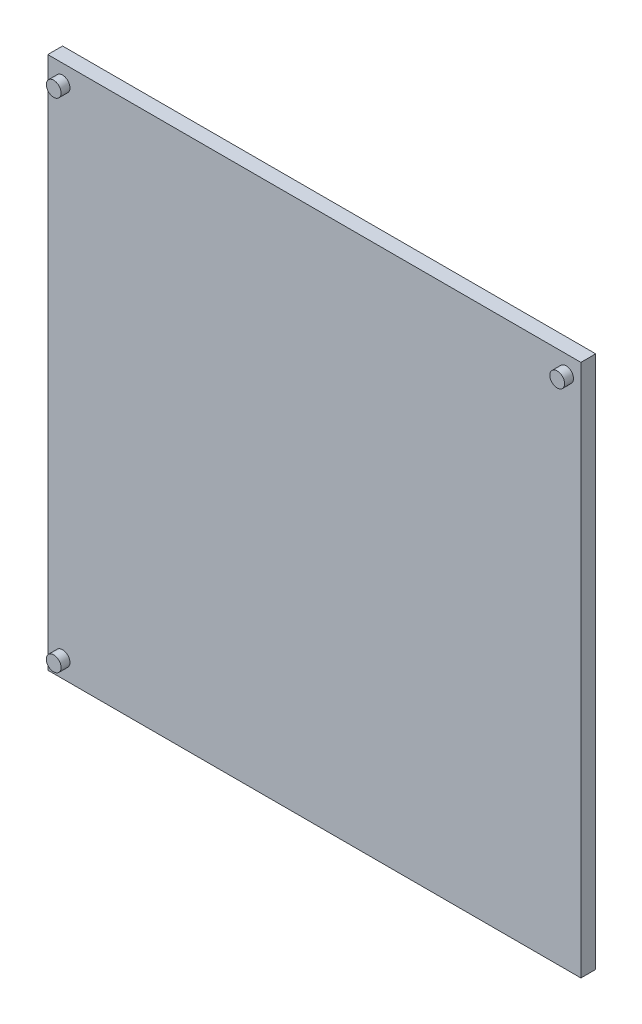
SolidWorks part; units mm, degrees
ref_plane "Front Plane" through (0, 0, 0) normal (0, 0, 1) x (1, 0, 0)
ref_plane "Top Plane" through (0, 0, 0) normal (0, 1, 0) x (1, 0, 0)
ref_plane "Right Plane" through (0, 0, 0) normal (1, 0, 0) x (0, 0, -1)
sketch "Sketch1" plane through (0, 0, 0) normal (0, 0, 1) x (1, 0, 0)
  line L1 (-45, -45) -> (45, -45)
  line L2 (-45, -45) -> (-45, 45)
  line L3 (-45, 45) -> (45, 45)
  line L4 (45, -45) -> (45, 45)
  line L5 (-45, -45) -> (45, 45) construction
  line L6 (-45, 45) -> (45, -45) construction
  point P0 (0, 0)
  dimension "D1" = 90
  dimension "D2" = 90
extrude "Boss-Extrude1" add sketch "Sketch1" along normal blind 2.5
sketch "Sketch2" plane through (0, 0, 2.5) normal (0, 0, 1) x (1, 0, 0)
  line L0 (0, 45) -> (0, -45) construction
  line L1 (45, 45) -> (-45, 45) construction
  line L2 (-45, -45) -> (45, -45) construction
  line L3 (-45, 0) -> (45, 0) construction
  line L4 (-45, 45) -> (-45, -45) construction
  line L5 (45, -45) -> (45, 45) construction
  circle A0 centre (-42.5, 42) radius 1.25
  circle A1 centre (42.5, 42) radius 1.25
  circle A3 centre (-42.5, -42) radius 1.25
  dimension "D1" = 2.5
  dimension "D2" = 3
  dimension "D3" = 2.5
extrude "Boss-Extrude2" add sketch "Sketch2" along normal blind 1.5
